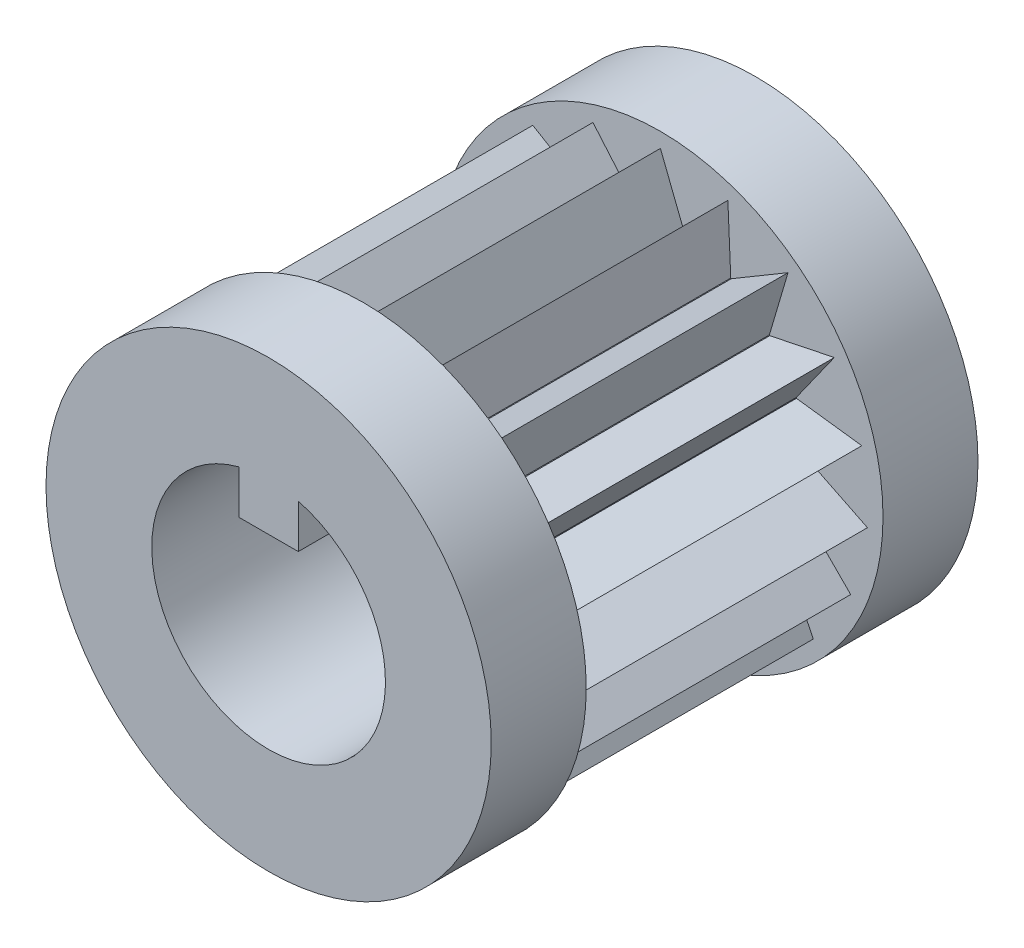
SolidWorks part; units mm, degrees
material "ABS"
ref_plane "Front Plane" through (0, 0, 0) normal (0, 0, 1) x (1, 0, 0)
ref_plane "Top Plane" through (0, 0, 0) normal (0, 1, 0) x (1, 0, 0)
ref_plane "Right Plane" through (0, 0, 0) normal (1, 0, 0) x (0, 0, -1)
sketch "Sketch1" plane through (0, 0, 0) normal (0, 0, 1) x (1, 0, 0)
  line L0 (0, 3.175) -> (0, 4.445) construction
  line L1 (0, 4.445) -> (0.5155, 3.1329)
  line L2 (0, 4.445) -> (-0.5155, 3.1329)
  line L3 (1.4433, 4.2042) -> (0.5296, 3.1305)
  line L4 (1.4433, 4.2042) -> (1.5048, 2.7957)
  line L5 (2.7302, 3.5077) -> (1.5174, 2.7889)
  line L6 (2.7302, 3.5077) -> (2.3311, 2.1556)
  line L7 (3.7212, 2.4312) -> (2.3408, 2.1451)
  line L8 (3.7212, 2.4312) -> (2.9047, 1.2819)
  line L9 (4.309, 1.0912) -> (2.9104, 1.2688)
  line L10 (4.309, 1.0912) -> (3.1636, 0.2693)
  line L11 (4.4298, -0.3671) -> (3.1647, 0.2551)
  line L12 (4.4298, -0.3671) -> (3.0796, -0.7725)
  line L13 (4.0706, -1.7855) -> (3.0761, -0.7864)
  line L14 (4.0706, -1.7855) -> (2.6619, -1.7306)
  line L15 (3.2703, -3.0105) -> (2.6541, -1.7425)
  line L16 (3.2703, -3.0105) -> (1.9558, -2.5011)
  line L17 (2.1156, -3.9093) -> (1.9445, -2.5099)
  line L18 (2.1156, -3.9093) -> (1.0377, -3.0006)
  line L19 (0.7316, -4.3844) -> (1.0241, -3.0053)
  line L20 (0.7316, -4.3844) -> (0.0072, -3.175)
  line L21 (-0.7316, -4.3844) -> (-0.0072, -3.175)
  line L22 (-0.7316, -4.3844) -> (-1.0241, -3.0053)
  line L23 (-2.1156, -3.9093) -> (-1.0377, -3.0006)
  line L24 (-2.1156, -3.9093) -> (-1.9445, -2.5099)
  line L25 (-3.2703, -3.0105) -> (-1.9558, -2.5011)
  line L26 (-3.2703, -3.0105) -> (-2.6541, -1.7425)
  line L27 (-4.0706, -1.7855) -> (-2.6619, -1.7306)
  line L28 (-4.0706, -1.7855) -> (-3.0761, -0.7864)
  line L29 (-4.4298, -0.3671) -> (-3.0796, -0.7725)
  line L30 (-4.4298, -0.3671) -> (-3.1647, 0.2551)
  line L31 (-4.309, 1.0912) -> (-3.1636, 0.2693)
  line L32 (-4.309, 1.0912) -> (-2.9104, 1.2688)
  line L33 (-3.7212, 2.4312) -> (-2.9047, 1.2819)
  line L34 (-3.7212, 2.4312) -> (-2.3408, 2.1451)
  line L35 (-2.7302, 3.5077) -> (-2.3311, 2.1556)
  line L36 (-2.7302, 3.5077) -> (-1.5174, 2.7889)
  line L37 (-1.4433, 4.2042) -> (-1.5048, 2.7957)
  line L38 (-1.4433, 4.2042) -> (-0.5296, 3.1305)
  arc A0 (-0.5155, 3.1329) -> (-0.5296, 3.1305) centre (0, 0) ccw
  arc A1 (-1.5048, 2.7957) -> (-1.5174, 2.7889) centre (0, 0) ccw
  arc A2 (-2.3311, 2.1556) -> (-2.3408, 2.1451) centre (0, 0) ccw
  arc A3 (-2.9047, 1.2819) -> (-2.9104, 1.2688) centre (0, 0) ccw
  arc A4 (-3.1636, 0.2693) -> (-3.1647, 0.2551) centre (0, 0) ccw
  arc A5 (-3.0796, -0.7725) -> (-3.0761, -0.7864) centre (0, 0) ccw
  arc A6 (-2.6619, -1.7306) -> (-2.6541, -1.7425) centre (0, 0) ccw
  arc A7 (-1.9558, -2.5011) -> (-1.9445, -2.5099) centre (0, 0) ccw
  arc A8 (-1.0377, -3.0006) -> (-1.0241, -3.0053) centre (0, 0) ccw
  arc A9 (-0.0072, -3.175) -> (0.0072, -3.175) centre (0, 0) ccw
  arc A10 (1.0241, -3.0053) -> (1.0377, -3.0006) centre (0, 0) ccw
  arc A11 (1.9445, -2.5099) -> (1.9558, -2.5011) centre (0, 0) ccw
  arc A12 (2.6541, -1.7425) -> (2.6619, -1.7306) centre (0, 0) ccw
  arc A13 (3.0761, -0.7864) -> (3.0796, -0.7725) centre (0, 0) ccw
  arc A14 (3.1647, 0.2551) -> (3.1636, 0.2693) centre (0, 0) ccw
  arc A15 (2.9104, 1.2688) -> (2.9047, 1.2819) centre (0, 0) ccw
  arc A16 (2.3408, 2.1451) -> (2.3311, 2.1556) centre (0, 0) ccw
  arc A17 (1.5174, 2.7889) -> (1.5048, 2.7957) centre (0, 0) ccw
  arc A18 (0.5296, 3.1305) -> (0.5155, 3.1329) centre (0, 0) ccw
  point P64 (0, 0)
  dimension "D1" = 6.35
  dimension "D2" = 1.27
  dimension "D3" = 19
extrude "Boss-Extrude1" add sketch "Sketch1" along normal blind 3.175 contours L2 A0 L38 L37 A1 L36 L35 A2 L34 L33 A3 L32 L31 A4 L30 L29 A5 L28 L27 A6 L26 L25 A7 L24 L23 A8 L22 L21 A9 L20 L19 A10 L18 L17 A11 L16 L15 A12 L14 L13 A13 L12 L11 A14 L10 L9 A15 L8 L7 A16 L6 L5 A17 L4 L3 A18 L1
sketch "Sketch2" plane through (0, 0, 0) normal (0, 0, -1) x (-1, 0, 0)
  circle A1 centre (0, 0) radius 4.7625
  dimension "D1" = 9.525
extrude "Boss-Extrude2" add sketch "Sketch2" along normal blind 2.032 contours A1
mirror "Mirror1" about plane through (0, 0, 3.175) normal (0, 0, 1) of bodies 102
sketch "Sketch3" plane through (0, 0, -2.032) normal (0, 0, -1) x (-1, 0, 0)
  line L2 (-0.635, 2.418) -> (-0.635, 1.484)
  line L3 (-0.635, 1.484) -> (0.635, 1.484)
  line L4 (0.635, 2.418) -> (0.635, 1.484)
  arc A0 (-0.635, 2.418) -> (0.635, 2.418) centre (0, 0) ccw
  point P3 (0, 2.5)
  dimension "D1" = 5
  dimension "D2" = 1.016
extrude "Cut-Extrude1" cut sketch "Sketch3" against normal blind 17.018 contours A0 L4 L3 L2
